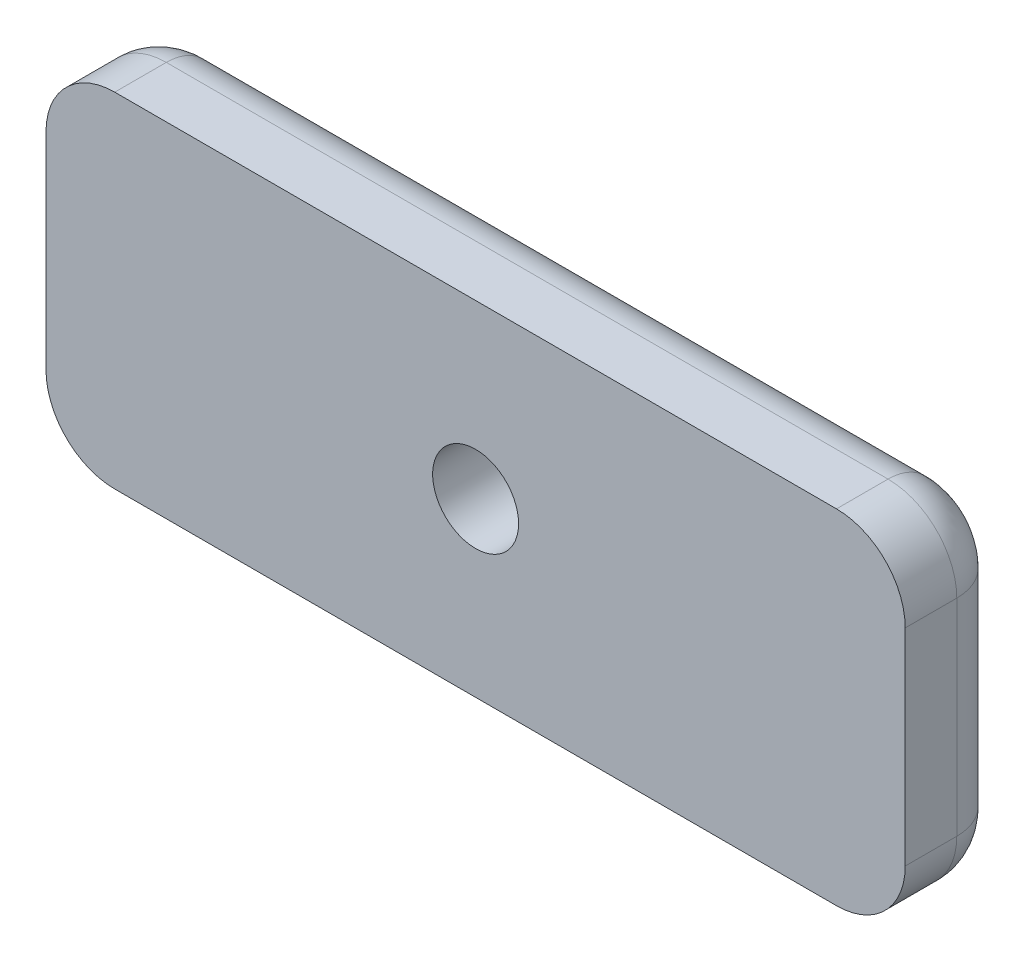
SolidWorks part; units mm, degrees
ref_plane "Front Plane" through (0, 0, 0) normal (0, 0, 1) x (1, 0, 0)
ref_plane "Top Plane" through (0, 0, 0) normal (0, 1, 0) x (1, 0, 0)
ref_plane "Right Plane" through (0, 0, 0) normal (1, 0, 0) x (0, 0, -1)
sketch "Sketch1" plane through (0, 0, 0) normal (0, 0, 1) x (1, 0, 0)
  line L1 (-21, 11.5842) -> (21, 11.5842)
  line L2 (-25, 7.5842) -> (-25, -4.4158)
  line L3 (-21, -8.4158) -> (21, -8.4158)
  line L4 (25, 7.5842) -> (25, -4.4158)
  circle A0 centre (0, 1.5842) radius 1 construction
  arc A1 (21, 11.5842) -> (25, 7.5842) centre (21, 7.5842) cw
  arc A2 (21, -8.4158) -> (25, -4.4158) centre (21, -4.4158) ccw
  arc A3 (-25, -4.4158) -> (-21, -8.4158) centre (-21, -4.4158) ccw
  arc A4 (-21, 11.5842) -> (-25, 7.5842) centre (-21, 7.5842) ccw
  circle A5 centre (0, 1.5842) radius 2.5
  point P8 (25, 11.5842)
  point P11 (25, -8.4158)
  dimension "D4" = 25
  dimension "D5" = 4
  dimension "D1" = 10
  dimension "D2" = 20
  dimension "D3" = 25
extrude "Boss-Extrude1" add sketch "Sketch1" along normal blind 6
fillet "Fillet1" radius 3 8 edges at (23.8284, -7.2442, 0) (0, -8.4158, 0) (-23.8284, -7.2442, 0) (-25, 1.5842, 0) (-23.8284, 10.4126, 0) (0, 11.5842, 0) (23.8284, 10.4126, 0) (25, 1.5842, 0)
